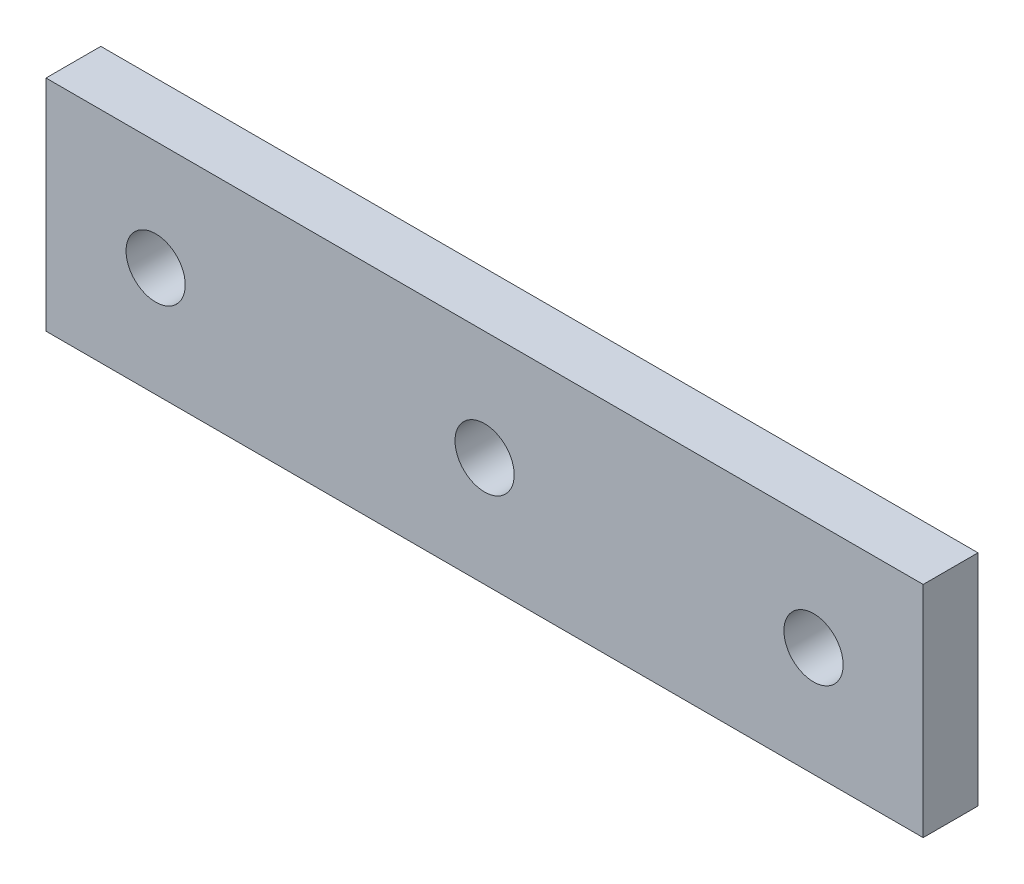
SolidWorks part; units mm, degrees
ref_plane "Front Plane" through (0, 0, 0) normal (0, 0, 1) x (1, 0, 0)
ref_plane "Top Plane" through (0, 0, 0) normal (0, 1, 0) x (1, 0, 0)
ref_plane "Right Plane" through (0, 0, 0) normal (1, 0, 0) x (0, 0, -1)
sketch "Sketch1" plane through (0, 0, 0) normal (0, 0, 1) x (1, 0, 0)
  line L0 (0, 12.7) -> (0, -12.7) construction
  line L1 (-50.8, -12.7) -> (50.8, -12.7)
  line L2 (-50.8, -12.7) -> (-50.8, 12.7)
  line L3 (-50.8, 12.7) -> (50.8, 12.7)
  line L4 (50.8, -12.7) -> (50.8, 12.7)
  line L5 (-50.8, -12.7) -> (50.8, 12.7) construction
  line L6 (-50.8, 12.7) -> (50.8, -12.7) construction
  circle A0 centre (0, 0) radius 3.429
  circle A1 centre (-38.1, 0) radius 3.429
  circle A2 centre (38.1, 0) radius 3.429
  point P0 (0, 0)
  dimension "D3" = 6.858
  dimension "D4" = 6.858
  dimension "D1" = 101.6
  dimension "D2" = 25.4
  dimension "D5" = 12.7
extrude "Boss-Extrude1" add sketch "Sketch1" along normal blind 6.35
